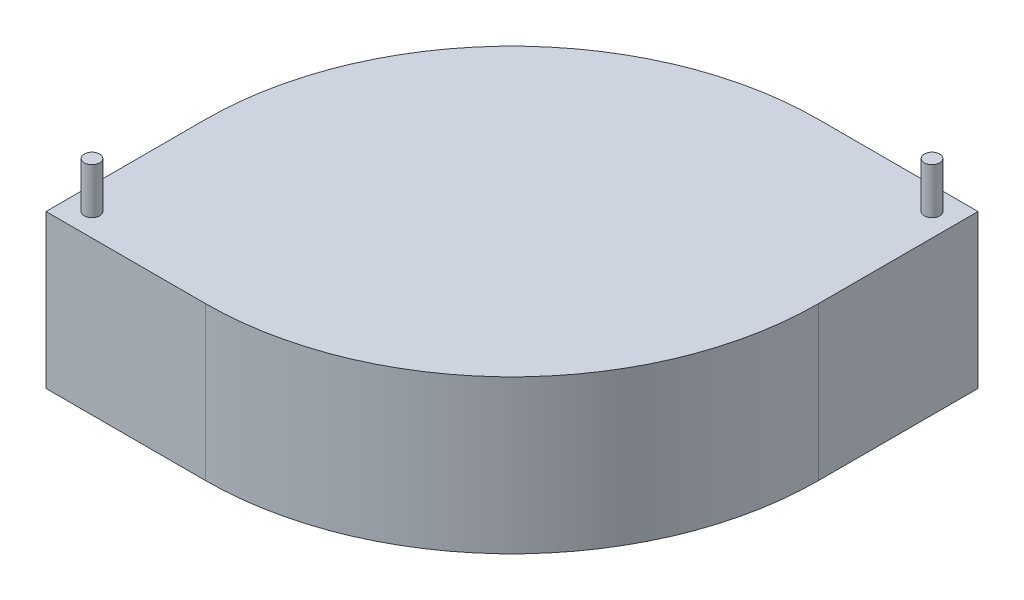
SolidWorks part; units mm, degrees
ref_plane "前基準面" through (0, 0, 0) normal (0, 0, 1) x (1, 0, 0)
ref_plane "上基準面" through (0, 0, 0) normal (0, 1, 0) x (1, 0, 0)
ref_plane "右基準面" through (0, 0, 0) normal (1, 0, 0) x (0, 0, -1)
sketch "草圖1" plane through (0, 0, 0) normal (0, 1, 0) x (1, 0, 0)
  line L1 (0, 0) -> (104, 0)
  line L2 (0, 0) -> (0, 104)
  line L3 (200, 304) -> (304, 304)
  line L4 (304, 200) -> (304, 304)
  arc A0 (104, 0) -> (304, 200) centre (104, 200) ccw
  arc A1 (0, 104) -> (200, 304) centre (200, 104) cw
  point P7 (304, 0)
  point P10 (0, 304)
  dimension "D3" = 200
  dimension "D1" = 304
  dimension "D2" = 304
extrude "填料-伸長1" add sketch "草圖1" along normal blind 100
sketch "草圖2" plane through (0, 100, 0) normal (0, 1, 0) x (1, 0, 0)
  line L0 (0, 0) -> (104, 0) construction
  line L1 (0, 104) -> (0, 0) construction
  line L2 (304, 200) -> (304, 304) construction
  line L3 (304, 304) -> (200, 304) construction
  circle A0 centre (15, 15) radius 5
  circle A1 centre (289, 289) radius 5
  dimension "D5" = 10
  dimension "D1" = 15
  dimension "D2" = 15
  dimension "D3" = 15
  dimension "D4" = 15
extrude "填料-伸長2" add sketch "草圖2" along normal blind 30
